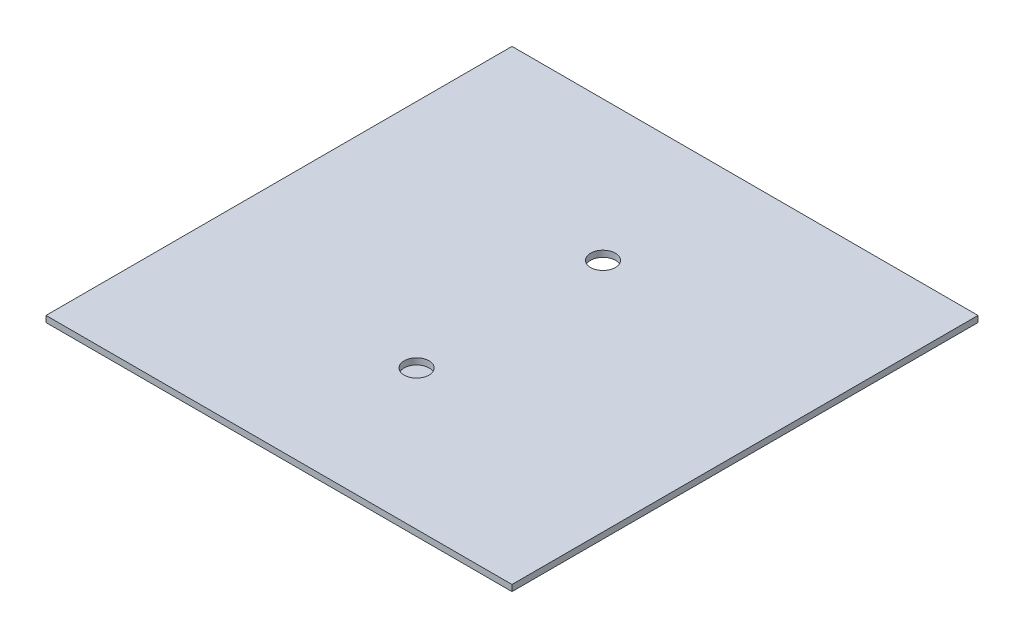
SolidWorks part; units mm, degrees
ref_plane "Front Plane" through (0, 0, 0) normal (0, 0, 1) x (1, 0, 0)
ref_plane "Top Plane" through (0, 0, 0) normal (0, 1, 0) x (1, 0, 0)
ref_plane "Right Plane" through (0, 0, 0) normal (1, 0, 0) x (0, 0, -1)
sketch "Sketch1" plane through (0, 0, 0) normal (0, 1, 0) x (1, 0, 0)
  circle A0 centre (0, 0) radius 40
  dimension "D1" = 80
extrude "Boss-Extrude1" add sketch "Sketch1" along normal blind 2
hole_wizard "Ø4.0mm Dowel Hole1" positions "Sketch3" profile "Sketch4" hole size "Ø4.0" standard "ANSI Metric"
sketch "Sketch3" plane through (0, 2, 0) normal (0, 1, 0) x (1, 0, 0)
  circle A0 centre (0, 0) radius 40 construction
  point P0 (0, 30)
  point P2 (0, -30)
  dimension "D1" = 60
  dimension "D2" = 30
sketch "Sketch4" plane through (0, 2, -30) normal (1, 0, 0) x (0, 0, 1)
  line L0 (0, 0) -> (0, 16.2017)
  line L1 (0, 16.2017) -> (2, 15)
  line L2 (2, 15) -> (2, 0)
  line L5 (2, 0) -> (0, 0)
  line L10 (0, 16.2017) -> (-2, 15) construction
  line L11 (0, -6.35) -> (0, 107.95) construction
  dimension "Hole Dia." = 4
  dimension "Hole Depth" = 15
  dimension "Drill Angle" = 118
sketch "Sketch9" plane through (0, 2, 0) normal (0, 1, 0) x (1, 0, 0)
  line L0 (0, 0) -> (-40, 0) construction
  line L1 (-40, 0) -> (40, 0) construction
  line L2 (40, 0) -> (0, 0) construction
  line L3 (0, 0) -> (20, 0) construction
  line L4 (20, 0) -> (20, -34.641) construction
  line L5 (20, 0) -> (20, 34.641) construction
  line L6 (12.5, 29.0474) -> (27.5, 29.0474)
  line L7 (-24.2906, -7.5) -> (-39.2906, -7.5)
  line L8 (-24.2906, -7.5) -> (-24.2906, 7.5)
  line L9 (-24.2906, 7.5) -> (-39.2906, 7.5)
  line L10 (-39.2906, -7.5) -> (-39.2906, 7.5)
  line L11 (-24.2906, -7.5) -> (-39.2906, 7.5) construction
  line L12 (-24.2906, 7.5) -> (-39.2906, -7.5) construction
  line L13 (12.5, -14.0474) -> (27.5, -14.0474)
  line L14 (12.5, -14.0474) -> (12.5, -29.0474)
  line L15 (12.5, -29.0474) -> (27.5, -29.0474)
  line L16 (27.5, -14.0474) -> (27.5, -29.0474)
  line L17 (12.5, -14.0474) -> (27.5, -29.0474) construction
  line L18 (12.5, -29.0474) -> (27.5, -14.0474) construction
  line L19 (27.5, 14.0474) -> (27.5, 29.0474)
  line L20 (12.5, 14.0474) -> (27.5, 14.0474)
  line L21 (12.5, 14.0474) -> (12.5, 29.0474)
  circle A0 centre (0, 0) radius 40 construction
  point P6 (-31.7906, 0)
  point P15 (20, -21.5474)
  dimension "D1" = 15
  dimension "D2" = 15
  dimension "D3" = 15
  dimension "D4" = 15
extrude "Boss-Extrude19" add sketch "Sketch9" along normal blind 20 contours L10 L7 L8 L9 | L16 L13 L14 L15 | L6 L19 L20 L21
sketch "Sketch10" plane through (0, 22, 0) normal (0, 1, 0) x (1, 0, 0)
  line L0 (-39.2906, -7.5) -> (-39.2906, 7.5) construction
  line L1 (-74.2906, 74.9979) -> (75.7094, 74.9979)
  line L2 (-74.2906, 74.9979) -> (-74.2906, -75.0021)
  line L3 (-74.2906, -75.0021) -> (75.7094, -75.0021)
  line L4 (75.7094, 74.9979) -> (75.7094, -75.0021)
  line L5 (12.5, 29.0474) -> (27.5, 29.0474) construction
  dimension "D1" = 150
  dimension "D2" = 150
  dimension "D3" = 35
  dimension "D4" = 45.9505
extrude "Boss-Extrude20" add sketch "Sketch10" along normal blind 2
sketch "Sketch11" plane through (0, 22, 0) normal (0, -1, 0) x (1, 0, 0)
  circle A0 centre (0, 30) radius 4
  circle A1 centre (0, -30) radius 4
  dimension "D1" = 8
  dimension "D2" = 8
extrude "Cut-Extrude1" cut sketch "Sketch11" against normal blind 2
fillet "Fillet2" radius 5 7 edges at (-31.7906, 22, -7.5) (-39.2906, 22, 0) (-31.7906, 22, 7.5) (20, 22, 29.0474) (27.5, 22, 21.5474) (27.5, 22, -21.5474) (20, 22, -29.0474)
